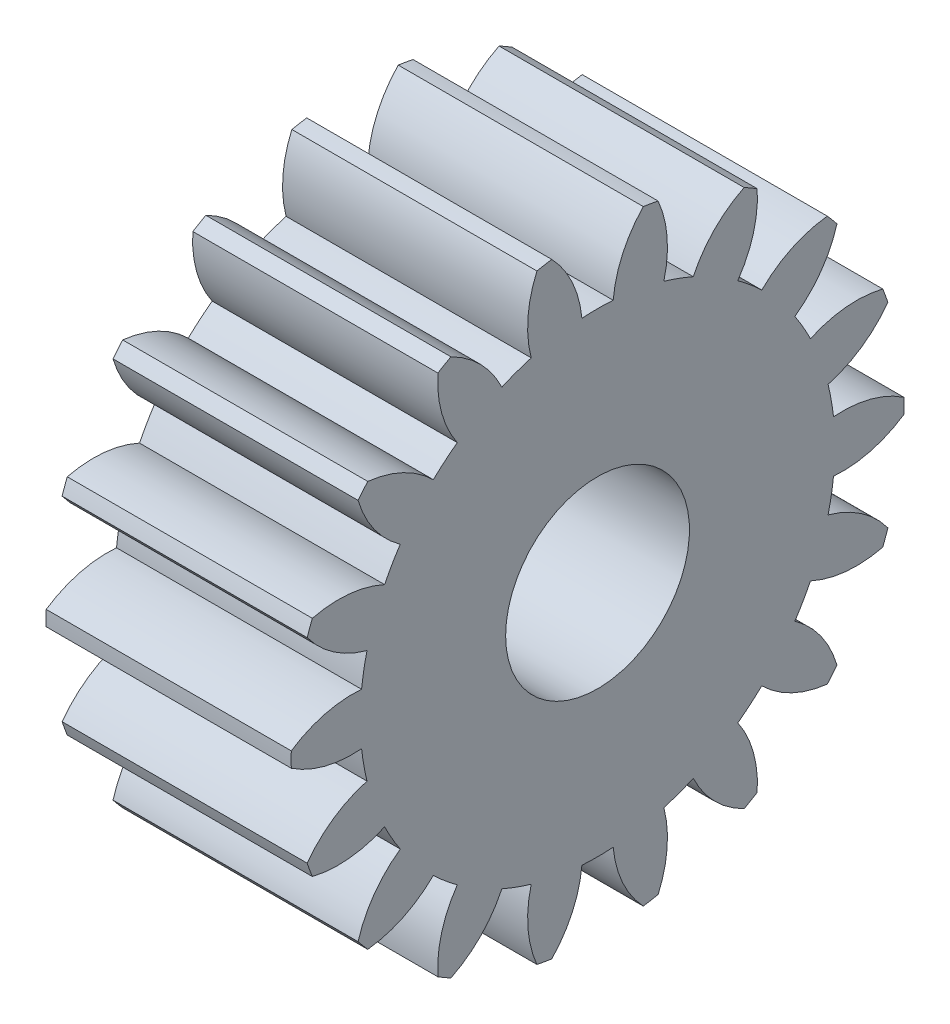
SolidWorks part; units mm, degrees
ref_plane "Plane1" through (0, 0, 0) normal (0, 0, 1) x (1, 0, 0)
ref_plane "Plane2" through (0, 0, 0) normal (0, 1, 0) x (1, 0, 0)
ref_plane "Plane3" through (0, 0, 0) normal (1, 0, 0) x (0, 0, -1)
sketch "HoldingSke" plane through (0, 0, 0) normal (0, 1, 0) x (1, 0, 0)
  line L0 (0, 0) -> (1.9021, -0.618)
  line L1 (-15, 0) -> (100, 0) construction
  line L2 (0, 0) -> (-2.1039, 2.3779)
  line L3 (0, 0) -> (-11.863, 4.5341)
  line L4 (0, 0) -> (8.2133, 2.6687)
  line L5 (0, 0) -> (-46.8476, -17.4728)
  line L6 (0, 0) -> (-3.3159, -2.2372)
  line L7 (-2.1039, 2.3779) -> (8.6586, 51.2059)
  line L8 (-76.2, 54.61) -> (-75.7, 54.61)
  line L9 (-71.009, 38.7566) -> (-53.1078, 45.2721)
  line L10 (-76.2, 71.12) -> (104.1128, 71.12)
  line L11 (0, 0) -> (-4, 0)
  line L12 (-76.2, 101.6) -> (-76.181, 101.6)
  line L13 (24.9733, 27.94) -> (52.9518, 28.4284)
  line L14 (24.9733, 27.94) -> (24.9743, 27.94)
  line L15 (24.9733, 27.94) -> (100.4006, 29.5858)
  line L16 (-63.627, -0.5) -> (-12.827, -0.5)
  circle A0 centre (0, 0) radius 1.5
  circle A1 centre (0, 0) radius 3.874
  circle A2 centre (0, 0) radius 37.5
  circle A3 centre (0, 0) radius 1.5
  dimension "MHD" = 7.748
  dimension "Hub_dia" = 75
  dimension "Bore" = 3
  dimension "MBD" = 3
  dimension "Num_teeth" = 18
  dimension "Pitch" = 2
  dimension "Overall_len" = 50
  dimension "Show_teeth" = 18
  dimension "Thickness" = 4
  dimension "OAL" = 50.0001
  dimension "T_dim" = 0.5
  dimension "Ap" = 20
  dimension "H" = 19.05
  dimension "Pitch_radius" = 180.3128
  dimension "Width" = 4
  dimension "Backlash" = 0.019
  dimension "Addendum_fac" = 1
  dimension "Dedendum_fac" = 1.25
  dimension "Clearance_fac" = 0.25
  dimension "Dedendum_add" = 0.001
  dimension "Module" = 0.5
sketch "BasProSke" plane through (0, 0, 0) normal (0, 1, 0) x (1, 0, 0)
  line L0 (-10, 0) -> (60, 0) construction
  line L1 (0, 0) -> (0, 5)
  line L2 (0, 0) -> (4, 0)
  line L3 (4, 0) -> (4, 5)
  line L4 (4, 5) -> (0, 5)
  dimension "Thickness" = 4
  dimension "Diameter" = 10
revolve "Base-Revolve" add sketch "BasProSke" angle 360 about L0
sketch "TooCutSke" plane through (0, 0, 0) normal (1, 0, 0) x (0, 0, -1)
  line L1 (0, 0) -> (0, 107) construction
  line L2 (0, 0) -> (-0.4254, 4.4798) construction
  line L3 (0, 0) -> (-1.5579, 8.835) construction
  line L4 (-0.4254, 4.4798) -> (-0.7789, 4.4175) construction
  arc A0 (0.2553, 3.8656) -> (-0.2553, 3.8656) centre (0, 0) ccw
  arc A1 (0.7686, 4.9663) -> (-0.7686, 4.9663) centre (0, 0) ccw
  circle A2 centre (0, 0) radius 4.5 construction
  circle A3 centre (0, 0) radius 4.2286 construction
  arc A4 (-0.2553, 3.8656) -> (-0.7686, 4.9663) centre (-2.0476, 3.6998) ccw
  arc A5 (0.7686, 4.9663) -> (0.2553, 3.8656) centre (2.0476, 3.6998) ccw
  dimension "Root_dia" = 7.748
  dimension "Overcut_dia" = 10.0508
  dimension "Pitch_dia" = 9
  dimension "Base_dia" = 8.4572
  dimension "Flank_rad" = 1.8
  dimension "Half_ang" = 10
  dimension "Half_CT" = 0.359
extrude "ToothCut" cut sketch "TooCutSke" along normal through all
fillet "Breaks" [suppressed] radius 0.01
fillet "RootFillets" [suppressed] radius 0.126
pattern_circular "TeethCuts" count 18 every 20 about axis through (-10, 0, 0) along (1, 0, 0) of "ToothCut", "RootFillets", "Breaks"
sketch "HubNeaOneSke" plane through (0, 0, 0) normal (-1, 0, 0) x (0, 0, 1)
  circle A0 centre (0, 0) radius 3.874
  dimension "Diameter" = 7.748
extrude "HubNearOne" [suppressed] add sketch "HubNeaOneSke" along normal blind 46.0001
sketch "HubNeaBotSke" plane through (0, 0, 0) normal (-1, 0, 0) x (0, 0, 1)
  circle A0 centre (0, 0) radius 3.874
  dimension "Diameter" = 7.748
extrude "HubNearBoth" [suppressed] add sketch "HubNeaBotSke" along normal blind 23
ref_plane "FarPln" through (4, 0, 0) normal (1, 0, 0) x (0, 0, -1)
sketch "HubFarSke" plane through (4, 0, 0) normal (1, 0, 0) x (0, 0, -1)
  circle A0 centre (0, 0) radius 3.874
  dimension "Diameter" = 7.748
extrude "HubFar" [suppressed] add sketch "HubFarSke" along normal blind 23
sketch "BorSke" plane through (0, 0, 0) normal (1, 0, 0) x (0, 0, -1)
  circle A0 centre (0, 0) radius 1.5
  dimension "Diameter" = 3
extrude "Bore" cut sketch "BorSke" along normal mid plane 100.0001
sketch "KeySke" plane through (0, 0, 0) normal (1, 0, 0) x (0, 0, -1)
  line L0 (-0.6, 0) -> (-0.6, 2)
  line L1 (-0.6, 2) -> (0.6, 2)
  line L2 (0.6, 2) -> (0.6, 0)
  line L3 (0, 0) -> (0, 34) construction
  line L4 (-0.6, 0) -> (0.6, 0)
  dimension "Offset" = 2
  dimension "Width" = 1.2
extrude "Keyway" [suppressed] cut sketch "KeySke" along normal mid plane 100.0001
pattern_circular "Keyway2" [suppressed] count 2 every 90 about axis through (-10, 0, 0) along (1, 0, 0)
equation "' \"Module@HoldingSke\" = 6.35"
equation "' \"Num_teeth@HoldingSke\" = 12"
equation "' \"Ap@HoldingSke\" =  20"
equation "' \"Ap@HoldingSke\" = 20"
equation "' \"Width@HoldingSke\" = 0.5 * 25.4"
equation "' \"Hub_dia@HoldingSke\"= 1 * 25.4"
equation "' \"Hub_dia@HoldingSke\" = 1 * 25.4"
equation "' \"Overall_len@HoldingSke\" = 1.0 * 25.4"
equation "' \"Bore@HoldingSke\" = 0.75 * 25.4"
equation "' \"T_dim@HoldingSke\" = 0.1 * 25.4"
equation "' \"Width@KeySke\" = 0.25 * 25.4"
equation "' \"Show_teeth@HoldingSke\" = 13"
equation "' \"Backlash@HoldingSke\" = 0.009 * 25.4"
equation "' \"Addendum_fac@HoldingSke\" = 1.0"
equation "' \"Dedendum_fac@HoldingSke\" = 1.25"
equation "' \"Dedendum_add@HoldingSke\" = 0.00005 * 25.4"
equation "' \"Clearance_fac@HoldingSke\" = 0.25"
equation "\"Pitch@HoldingSke\" = 1 / \"Module@HoldingSke\""
equation "\"Overcut_dia@TooCutSke\" = (\"Num_teeth@HoldingSke\" + 2 * \"Addendum_fac@HoldingSke\") / \"Pitch@HoldingSke\" + 0.002 * 25.4"
equation "\"Pitch_dia@TooCutSke\" = \"Num_teeth@HoldingSke\" / \"Pitch@HoldingSke\""
equation "\"Base_dia@TooCutSke\" = \"Num_teeth@HoldingSke\" / \"Pitch@HoldingSke\" * cos((\"Ap@HoldingSke\"  * 3.14159265 / 180))"
equation "\"Root_dia@TooCutSke\" = (\"Num_teeth@HoldingSke\" + 2) / \"Pitch@HoldingSke\" - 2 * (\"Addendum_fac@HoldingSke\" + \"Dedendum_fac@HoldingSke\") / \"Pitch@HoldingSke\" - \"Dedendum_add@HoldingSke\" * 2"
equation "\"Half_ang@TooCutSke\" = 180 / \"Num_teeth@HoldingSke\""
equation "\"Half_CT@TooCutSke\" = \"Num_teeth@HoldingSke\" / \"Pitch@HoldingSke\" * sin((3.14159265 / 2 / \"Num_teeth@HoldingSke\")) / 2 - 7 * \"Backlash@HoldingSke\" / 4"
equation "\"Flank_rad@TooCutSke\" = \"Num_teeth@HoldingSke\" / \"Pitch@HoldingSke\" / 5"
equation "\"Radius@RootFillets\" = \"Clearance_fac@HoldingSke\" / \"Pitch@HoldingSke\" + \"Dedendum_add@HoldingSke\""
equation "\"Break_rad@Breaks\" = 0.02 / \"Pitch@HoldingSke\""
equation "\"Thickness@HoldingSke\" = \"Width@HoldingSke\""
equation "\"OAL@HoldingSke\" = \"Thickness@HoldingSke\""
equation "\"MHD@HoldingSke\" = (\"Num_teeth@HoldingSke\" + 2) / \"Pitch@HoldingSke\" - 2 * (\"Addendum_fac@HoldingSke\" + \"Dedendum_fac@HoldingSke\")  / \"Pitch@HoldingSke\" - \"Dedendum_add@HoldingSke\" * 2"
equation "\"MBD@HoldingSke\" = (\"Num_teeth@HoldingSke\" + 2) / \"Pitch@HoldingSke\" - 2 * (\"Addendum_fac@HoldingSke\" + \"Dedendum_fac@HoldingSke\")  / \"Pitch@HoldingSke\" - \"Dedendum_add@HoldingSke\" * 2 - 0.002 * 25.4"
equation "\"MHD@HoldingSke\" = ((sgn( \"MHD@HoldingSke\" - \"Hub_dia@HoldingSke\" )-1)*( \"MHD@HoldingSke\" - \"Hub_dia@HoldingSke\" ))/-2+ \"Hub_dia@HoldingSke\""
equation "\"MBD@HoldingSke\" = ((sgn( \"MBD@HoldingSke\" - \"Bore@HoldingSke\" )-1)*( \"MBD@HoldingSke\" - \"Bore@HoldingSke\" ))/-2+ \"Bore@HoldingSke\""
equation "\"OAL@HoldingSke\" = ((sgn( \"OAL@HoldingSke\" - \"Overall_len@HoldingSke\" )+1)*( \"OAL@HoldingSke\" - \"Overall_len@HoldingSke\" ))/2 + \"Overall_len@HoldingSke\" + 0.000002 * 25.4"
equation "\"Num_teeth@TeethCuts\" = int( \"Show_teeth@HoldingSke\" ) + 1"
equation "\"Num_teeth@TeethCuts\" = ((sgn( \"Num_teeth@TeethCuts\" - \"Num_teeth@HoldingSke\" )-1)*( \"Num_teeth@TeethCuts\" - \"Num_teeth@HoldingSke\" ))/-2+ \"Num_teeth@HoldingSke\""
equation "\"Num_teeth@TeethCuts\" = ((sgn( \"Num_teeth@TeethCuts\" - 2.0)+1)*( \"Num_teeth@TeethCuts\" - 2.0))/2 +2.0"
equation "\"Angle@TeethCuts\" = 360.0 / \"Num_teeth@HoldingSke\""
equation "\"Diameter@BasProSke\" = (\"Num_teeth@HoldingSke\" + 2 * \"Addendum_fac@HoldingSke\") / \"Pitch@HoldingSke\""
equation "\"Thickness@BasProSke\"  = \"Thickness@HoldingSke\""
equation "' \"Fillet_rad@BasProSke\" =  \"Thickness@HoldingSke\" * 0.05"
equation "' \"Fillet_rad@BasProSke\" = \"Thickness@HoldingSke\" * 0.05"
equation "\"MHD@HoldingSke\" = ((sgn( \"MHD@HoldingSke\" - \"Root_dia@TooCutSke\" )-1)*( \"MHD@HoldingSke\" - \"Root_dia@TooCutSke\" ))/-2+ \"Root_dia@TooCutSke\""
equation "\"Diameter@HubNeaOneSke\" = \"MHD@HoldingSke\""
equation "\"Length@HubNearOne\" = \"OAL@HoldingSke\" - \"Thickness@BasProSke\""
equation "\"Diameter@HubNeaBotSke\" = \"MHD@HoldingSke\""
equation "\"Length@HubNearBoth\" = ( \"OAL@HoldingSke\" - \"Thickness@BasProSke\" ) / 2.0"
equation "\"Thickness@FarPln\" = \"Thickness@BasProSke\""
equation "\"Diameter@HubFarSke\" = \"MHD@HoldingSke\""
equation "\"Length@HubFar\" = ( \"OAL@HoldingSke\" - \"Thickness@BasProSke\" ) / 2.0"
equation "\"Diameter@BorSke\" = \"MBD@HoldingSke\""
equation "\"D1@Bore\" = \"OAL@HoldingSke\" * 2.0"
equation "\"D1@Keyway\" = \"OAL@HoldingSke\" * 2.0"
equation "\"Offset@KeySke\" = \"T_dim@HoldingSke\" + \"MBD@HoldingSke\" / 2.0"
